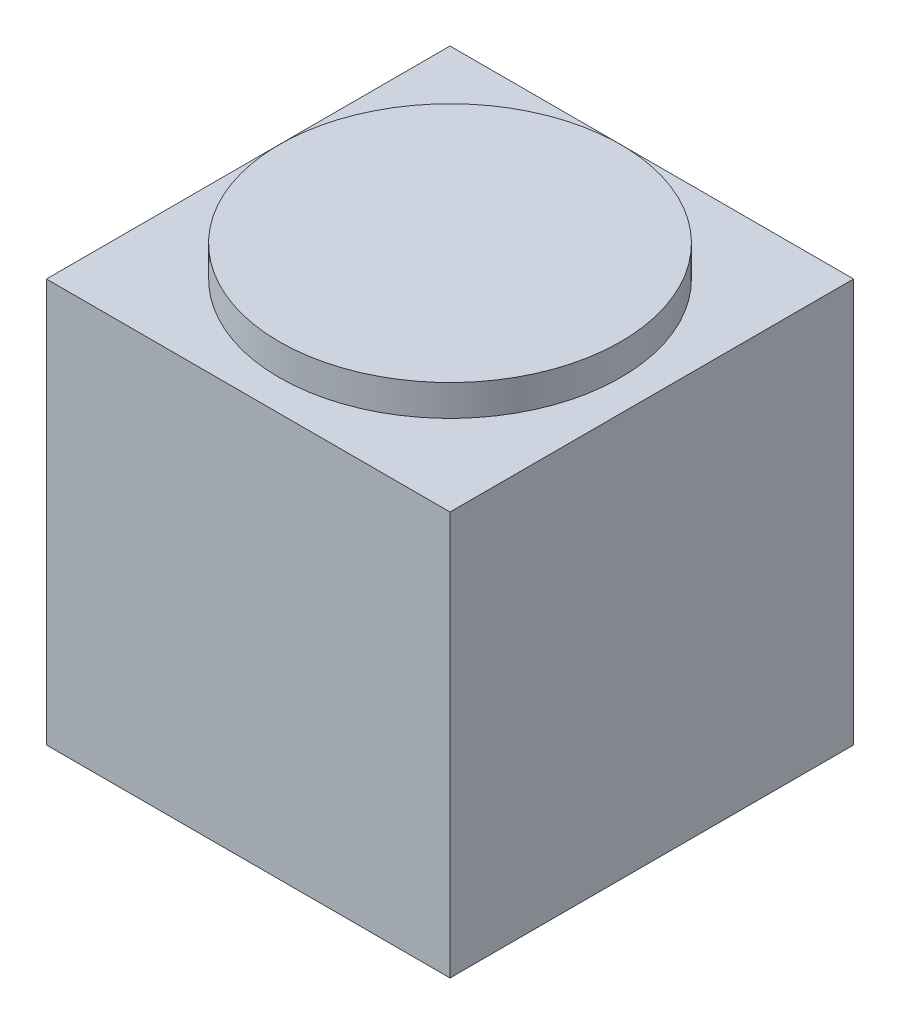
SolidWorks part; units mm, degrees
ref_plane "Front Plane" through (0, 0, 0) normal (0, 0, 1) x (1, 0, 0)
ref_plane "Top Plane" through (0, 0, 0) normal (0, 1, 0) x (1, 0, 0)
ref_plane "Right Plane" through (0, 0, 0) normal (1, 0, 0) x (0, 0, -1)
sketch "Sketch1" plane through (0, 0, 0) normal (0, 1, 0) x (1, 0, 0)
  line L0 (65, -65) -> (-65, 65) construction
  line L1 (-65, 65) -> (65, 65)
  line L2 (-65, 65) -> (-65, -65)
  line L3 (-65, -65) -> (65, -65)
  line L4 (65, 65) -> (65, -65)
  dimension "D1" = 130
extrude "Boss-Extrude1" add sketch "Sketch1" along normal mid plane 130
sketch "Sketch2" plane through (0, 65, 0) normal (0, 1, 0) x (1, 0, 0)
  circle A0 centre (0, 0) radius 55
  dimension "D1" = 110
extrude "Boss-Extrude2" add sketch "Sketch2" along normal blind 10
